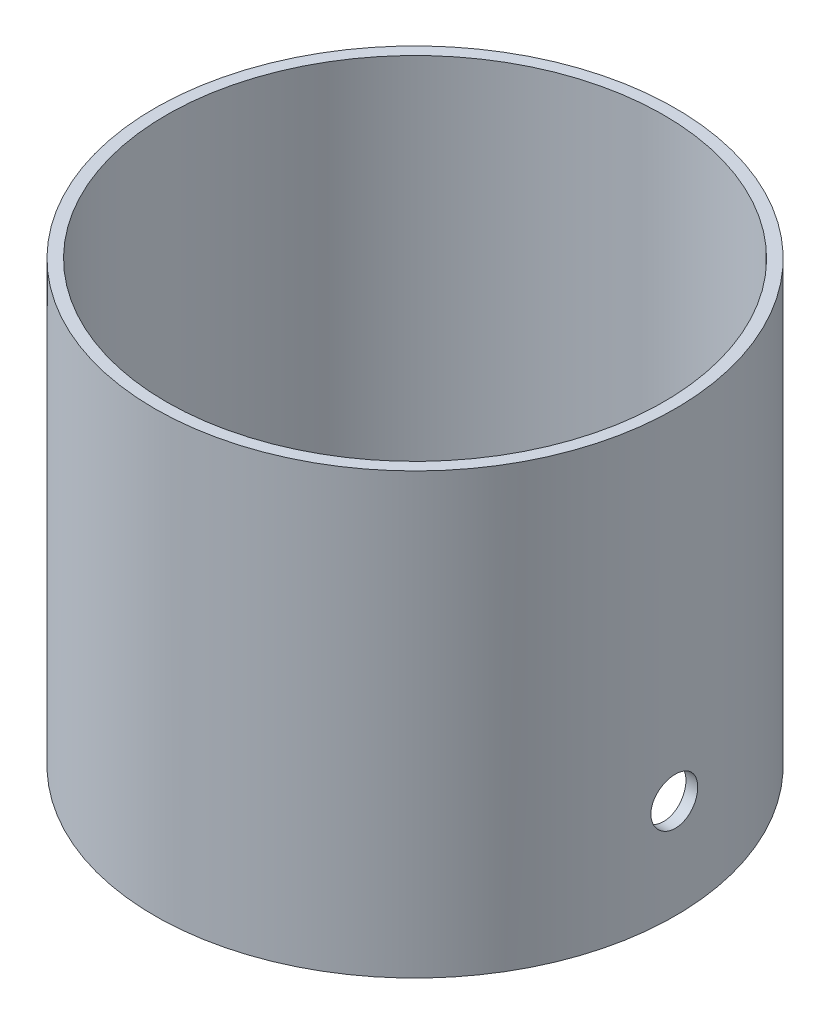
SolidWorks part; units mm, degrees
ref_plane "Front Plane" through (0, 0, 0) normal (0, 0, 1) x (1, 0, 0)
ref_plane "Top Plane" through (0, 0, 0) normal (0, 1, 0) x (1, 0, 0)
ref_plane "Right Plane" through (0, 0, 0) normal (1, 0, 0) x (0, 0, -1)
sketch "Sketch1" plane through (0, 0, 0) normal (0, 1, 0) x (1, 0, 0)
  circle A0 centre (0, 0) radius 44.45
  circle A1 centre (0, 0) radius 42.45
  dimension "D1" = 88.9
  dimension "D2" = 2
extrude "Boss-Extrude1" add sketch "Sketch1" along normal mid plane 75
sketch "Sketch2" plane through (0, 0, 0) normal (1, 0, 0) x (0, 0, -1)
  line L0 (0, 0) -> (0, -37.5) construction
  line L1 (-44.45, -37.5) -> (44.45, -37.5) construction
  line L3 (4, -45.5) -> (-4, -45.5)
  line L4 (4, -45.5) -> (4, -29.5)
  line L5 (4, -29.5) -> (-4, -29.5)
  line L6 (-4, -45.5) -> (-4, -29.5)
  line L7 (4, -45.5) -> (-4, -29.5) construction
  line L8 (4, -29.5) -> (-4, -45.5) construction
  dimension "D1" = 8
  dimension "D2" = 8
extrude "Cut-Extrude1" cut sketch "Sketch2" against normal up to surface (44.2697 mm away)
sketch "Sketch3" plane through (0, 0, 0) normal (1, 0, 0) x (0, 0, -1)
  circle A2 centre (0, -20.55) radius 4
  dimension "D1" = 8
extrude "Cut-Extrude2" cut sketch "Sketch3" along normal through all
